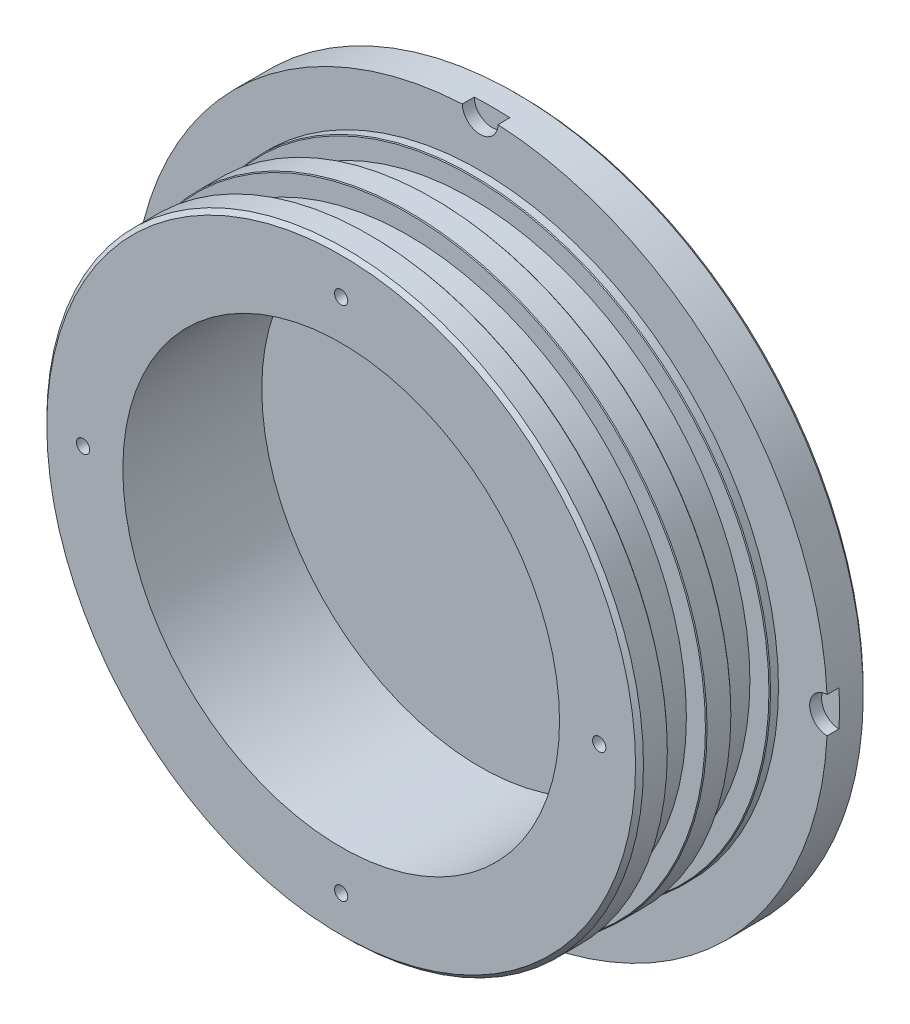
SolidWorks part; units mm, degrees
material "AISI 316 Barre d'acier inoxydable recuit (SS)"
ref_plane "Plan de face" through (0, 0, 0) normal (0, 0, 1) x (1, 0, 0)
ref_plane "Plan de dessus" through (0, 0, 0) normal (0, 1, 0) x (1, 0, 0)
ref_plane "Plan de droite" through (0, 0, 0) normal (1, 0, 0) x (0, 0, -1)
sketch "Esquisse1" plane through (0, 0, 0) normal (0, 1, 0) x (1, 0, 0)
  line L0 (87.5, 159.225) -> (0, 159.225)
  line L1 (0, 159.225) -> (0, 114.225)
  line L2 (0, 114.225) -> (75.15, 114.225)
  line L3 (75.15, 114.225) -> (75.15, 121.425)
  line L4 (75.15, 121.425) -> (70.15, 121.425)
  line L5 (70.15, 121.425) -> (70.15, 131.025)
  line L6 (70.15, 131.025) -> (75.15, 131.025)
  line L7 (75.15, 131.025) -> (75.15, 137.425)
  line L8 (75.15, 137.425) -> (70.15, 137.425)
  line L9 (70.15, 137.425) -> (70.15, 147.025)
  line L10 (70.15, 147.025) -> (75.15, 147.025)
  line L11 (75.15, 147.025) -> (75.15, 149.225)
  line L12 (75.15, 149.225) -> (87.5, 149.225)
  line L13 (87.5, 149.225) -> (87.5, 159.225)
  line L14 (0, 159.225) -> (0, 114.225) construction
revolve "Révolution1" add sketch "Esquisse1" angle 360 about L14
hole_wizard "Diamètre du perçage Ø9.0 (9)1" positions "Esquisse3" profile "Esquisse2" hole size "Ø9.0" standard "Ansi Metric"
sketch "Esquisse3" plane through (0, 0, -149.225) normal (0, 0, 1) x (1, 0, 0)
  point P0 (-87.5, 0)
  point P1 (0, 87.5)
  point P2 (0, -87.5)
  point P3 (87.5, 0)
sketch "Esquisse2" plane through (-87.5, 0, -149.225) normal (1, 0, 0) x (0, -1, 0)
  line L0 (0, 0) -> (0, 3)
  line L1 (0, 3) -> (4.5, 3)
  line L2 (4.5, 3) -> (4.5, 0)
  line L5 (4.5, 0) -> (0, 0)
  line L10 (0, 3) -> (-4.5, 3) construction
  line L11 (0, -6.35) -> (0, 107.95) construction
  dimension "Diamètre du perçage" = 9
  dimension "Profondeur du perçage" = 3
  dimension "Angle de pointe" = 180
hole_wizard "Dégagement M31" positions "Esquisse5" profile "Esquisse4" hole size "M3" standard "Ansi Metric"
sketch "Esquisse5" plane through (0, 0, -114.225) normal (0, 0, 1) x (1, 0, 0)
  point P0 (-65, 0)
  point P1 (65, 0)
  point P2 (0, 65)
  point P3 (0, -65)
sketch "Esquisse4" plane through (-65, 0, -114.225) normal (1, 0, 0) x (0, -1, 0)
  line L0 (0, 0) -> (0, 17.001)
  line L1 (0, 17.001) -> (1.666, 16)
  line L2 (1.666, 16) -> (1.666, 0)
  line L5 (1.666, 0) -> (0, 0)
  line L10 (0, 17.001) -> (-1.666, 16) construction
  line L11 (0, -6.35) -> (0, 107.95) construction
  dimension "Diamètre du perçage" = 3.332
  dimension "Profondeur du perçage" = 16
  dimension "Angle de pointe" = 118
hole_wizard "Dégagement M1001" positions "Esquisse7" profile "Esquisse6" hole size "M100" standard "Ansi Metric"
sketch "Esquisse7" plane through (0, 0, -114.225) normal (0, 0, 1) x (1, 0, 0)
  point P0 (0, 0)
sketch "Esquisse6" plane through (0, 0, -114.225) normal (1, 0, 0) x (0, -1, 0)
  line L0 (0, 0) -> (0, 35)
  line L1 (0, 35) -> (55, 35)
  line L2 (55, 35) -> (55, 0)
  line L5 (55, 0) -> (0, 0)
  line L10 (0, 35) -> (-55, 35) construction
  line L11 (0, -6.35) -> (0, 107.95) construction
  dimension "Diamètre du perçage" = 110
  dimension "Profondeur du perçage" = 35
  dimension "Angle de pointe" = 180
chamfer "Chanfrein1" distance 0.2 angle 45 4 edges at (75.15, 0, -147.025) (75.15, 0, -121.425) (75.15, 0, -131.025) (75.15, 0, -137.425)
chamfer "Chanfrein2" distance 1 angle 45 2 edges at (87.5, 0, -159.225) (75.15, 0, -114.225)
